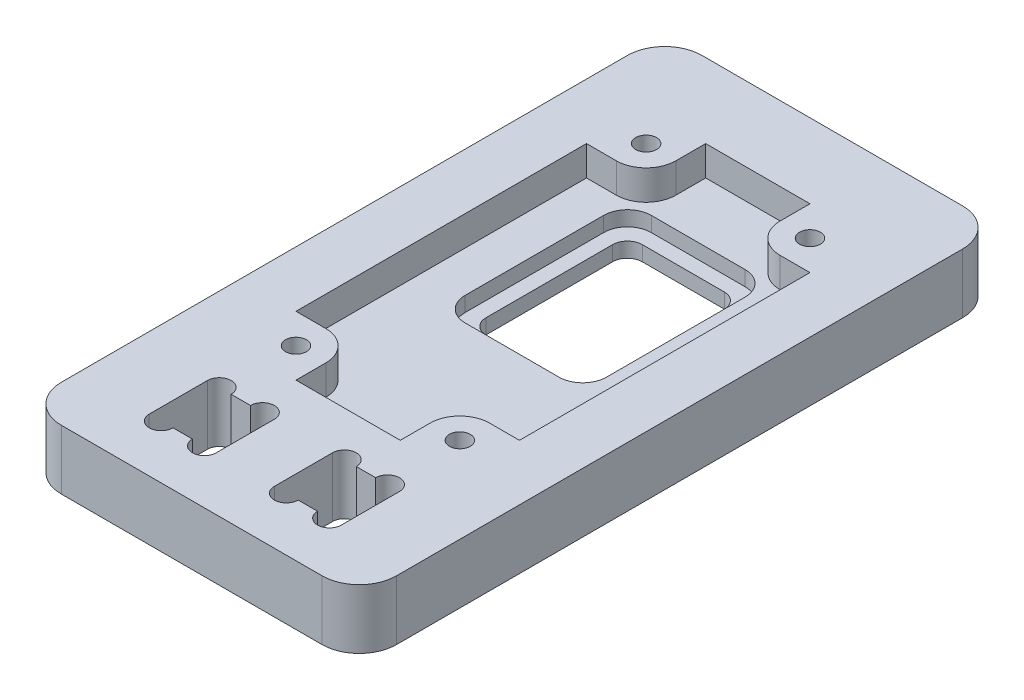
SolidWorks part; units mm, degrees
ref_plane "Front Plane" through (0, 0, 0) normal (0, 0, 1) x (1, 0, 0)
ref_plane "Top Plane" through (0, 0, 0) normal (0, 1, 0) x (1, 0, 0)
ref_plane "Right Plane" through (0, 0, 0) normal (1, 0, 0) x (0, 0, -1)
sketch "Sketch1" plane through (0, 0, 0) normal (0, 1, 0) x (1, 0, 0)
  line L0 (7.5, 21) -> (7.5, 41) construction
  line L1 (2, 0) -> (13, 0)
  line L2 (0, 2) -> (0, 19)
  line L3 (2, 21) -> (13, 21)
  line L4 (15, 2) -> (15, 19)
  line L5 (3.6, -30) -> (11.4, -30) construction
  line L6 (-10, 41) -> (25, 41)
  line L7 (-15, 36) -> (-15, -40)
  line L8 (-10, -45) -> (25, -45)
  line L9 (30, 36) -> (30, -40)
  line L10 (-5.4, -30) -> (3.6, -30)
  line L11 (-5.4, -30) -> (-5.4, -37.8)
  line L12 (-5.4, -37.8) -> (3.6, -37.8)
  line L13 (3.6, -30) -> (3.6, -37.8)
  line L14 (11.4, -30) -> (20.4, -30)
  line L15 (11.4, -30) -> (11.4, -37.8)
  line L16 (11.4, -37.8) -> (20.4, -37.8)
  line L17 (20.4, -30) -> (20.4, -37.8)
  line L18 (7.5, 0) -> (7.5, -45) construction
  arc A0 (13, 0) -> (15, 2) centre (13, 2) ccw
  arc A1 (2, 0) -> (0, 2) centre (2, 2) cw
  arc A2 (15, 19) -> (13, 21) centre (13, 19) ccw
  arc A3 (0, 19) -> (2, 21) centre (2, 19) cw
  arc A4 (30, 36) -> (25, 41) centre (25, 36) ccw
  arc A5 (25, -45) -> (30, -40) centre (25, -40) ccw
  arc A6 (-10, -45) -> (-15, -40) centre (-10, -40) cw
  arc A7 (-15, 36) -> (-10, 41) centre (-10, 36) cw
  circle A8 centre (-3.8, -30) radius 1.6
  circle A9 centre (2, -30) radius 1.6
  circle A10 centre (-3.8, -37.8) radius 1.6
  circle A11 centre (2, -37.8) radius 1.6
  circle A12 centre (13, -30) radius 1.6
  circle A13 centre (18.8, -30) radius 1.6
  circle A14 centre (13, -37.8) radius 1.6
  circle A15 centre (18.8, -37.8) radius 1.6
  point P9 (0, 0)
  point P12 (15, 21)
  point P15 (0, 21)
  point P22 (7.5, 41)
  point P41 (7.5, -30)
  dimension "D3" = 2
  dimension "D6" = 5
  dimension "D14" = 3.2
  dimension "D15" = 3.2
  dimension "D16" = 3.2
  dimension "D17" = 3.2
  dimension "D18" = 3.2
  dimension "D19" = 3.2
  dimension "D20" = 3.2
  dimension "D21" = 3.2
  dimension "D1" = 21
  dimension "D2" = 15
  dimension "D4" = 20
  dimension "D5" = 45
  dimension "D7" = 35
  dimension "D8" = 7.8
  dimension "D9" = 7.8
  dimension "D10" = 15
  dimension "D11" = 9
  dimension "D12" = 9
  dimension "D13" = 7.8
extrude "Boss-Extrude1" add sketch "Sketch1" along normal blind 8 contours A7 L7 A6 L8 A5 L9 A4 L6 A15 L16 A14 L15 A12 L14 A13 L17 A11 L12 A10 L11 A8 L10 A9 L13 L2 A3 L3 A2 L4 A0 L1 A1
sketch "Sketch3" plane through (0, 8, 0) normal (0, 1, 0) x (1, 0, 0)
  line L0 (7.5, 31) -> (7.5, 21) construction
  line L1 (-7.5, 31) -> (22.5, 31)
  line L2 (-7.5, 31) -> (-7.5, -24)
  line L3 (-7.5, -24) -> (22.5, -24)
  line L4 (22.5, 31) -> (22.5, -24)
  line L5 (2, 21) -> (13, 21) construction
  line L6 (0.5, 27) -> (0.5, 31)
  line L7 (-3.5, 23) -> (-7.5, 23)
  line L8 (14.5, 27) -> (14.5, 31)
  line L9 (18.5, 23) -> (22.5, 23)
  line L10 (0.5, -20) -> (0.5, -24)
  line L11 (14.5, -20) -> (14.5, -24)
  line L12 (18.5, -16) -> (22.5, -16)
  line L13 (-3.5, -16) -> (-7.5, -16)
  circle A0 centre (-3.5, 27) radius 4
  circle A1 centre (18.5, 27) radius 4
  circle A2 centre (-3.5, -20) radius 4
  circle A3 centre (18.5, -20) radius 4
  circle A4 centre (-3.5, 27) radius 1.4
  circle A5 centre (18.5, 27) radius 1.4
  circle A6 centre (-3.5, -20) radius 1.4
  circle A7 centre (18.5, -20) radius 1.4
  dimension "D4" = 8
  dimension "D5" = 8
  dimension "D6" = 8
  dimension "D7" = 8
  dimension "D8" = 2.8
  dimension "D9" = 2.8
  dimension "D10" = 2.8
  dimension "D11" = 2.8
  dimension "D1" = 55
  dimension "D2" = 30
  dimension "D3" = 10
extrude "Cut-Extrude1" cut sketch "Sketch3" against normal blind 4
sketch "Sketch5" plane through (0, 4, 0) normal (0, 1, 0) x (1, 0, 0)
  line L0 (7.5, 0) -> (7.5, -2) construction
  line L1 (1.2, -2) -> (13.8, -2)
  line L2 (-2, 1.2) -> (-2, 19.8)
  line L3 (1.2, 23) -> (13.8, 23)
  line L4 (17, 1.2) -> (17, 19.8)
  line L5 (13, 0) -> (2, 0) construction
  line L7 (2, 21) -> (13, 21) construction
  line L8 (0, 2) -> (0, 19) construction
  line L10 (0, 10.5) -> (-2, 10.5) construction
  arc A0 (-2, 1.2) -> (1.2, -2) centre (1.2, 1.2) ccw
  arc A1 (17, 19.8) -> (13.8, 23) centre (13.8, 19.8) ccw
  arc A2 (-2, 19.8) -> (1.2, 23) centre (1.2, 19.8) cw
  arc A3 (13.8, -2) -> (17, 1.2) centre (13.8, 1.2) ccw
  dimension "D1" = 3.2
  dimension "D4" = 3.2
  dimension "D5" = 3.2
  dimension "D2" = 2
  dimension "D3" = 2
extrude "Cut-Extrude2" cut sketch "Sketch5" against normal blind 2
